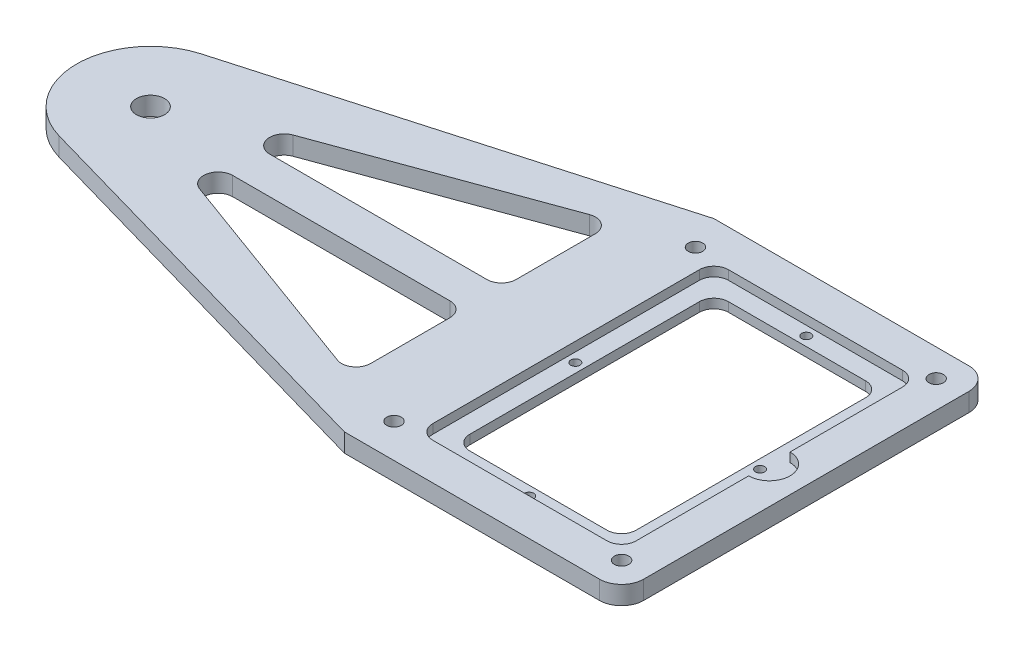
SolidWorks part; units mm, degrees
material "UHMW"
ref_plane "Front Plane" through (0, 0, 0) normal (0, 0, 1) x (1, 0, 0)
ref_plane "Top Plane" through (0, 0, 0) normal (0, 1, 0) x (1, 0, 0)
ref_plane "Right Plane" through (0, 0, 0) normal (1, 0, 0) x (0, 0, -1)
sketch "Sketch1" plane through (0, 0, 0) normal (0, 1, 0) x (1, 0, 0)
  line L0 (-47.625, 0) -> (47.625, 0) construction
  line L1 (-47.625, -63.5) -> (47.625, -63.5)
  line L2 (-47.625, -63.5) -> (-47.625, 63.5)
  line L3 (-47.625, 63.5) -> (47.625, 63.5)
  line L4 (47.625, -63.5) -> (47.625, 63.5)
  line L5 (-47.625, -63.5) -> (47.625, 63.5) construction
  line L6 (-47.625, 63.5) -> (47.625, -63.5) construction
  point P0 (0, 0)
  dimension "D1" = 95.25
  dimension "D2" = 127
  dimension "D3" = 63.5
extrude "Boss-Extrude1" add sketch "Sketch1" along normal blind 6.35
sketch "Sketch4" plane through (0, 6.35, 0) normal (0, 1, 0) x (1, 0, 0)
  line L1 (-47.625, 63.5) -> (-184.7599, 24.4278)
  line L5 (-47.625, 63.5) -> (-47.625, -63.5) construction
  line L9 (-47.625, -63.5) -> (-184.7599, -24.4278)
  line L10 (-47.625, 63.5) -> (-47.625, -63.5)
  arc A0 (-184.7599, 24.4278) -> (-184.7599, -24.4278) centre (-177.8, 0) ccw
  dimension "D1" = 50.8
  dimension "D2" = 177.8
extrude "Boss-Extrude3" add sketch "Sketch4" against normal blind 6.35
sketch "Sketch5" plane through (0, 6.35, 0) normal (0, 1, 0) x (1, 0, 0)
  circle A0 centre (-177.8, 0) radius 4.826
  circle A1 centre (-22.225, 0) radius 4.826
  arc A2 (-184.7599, 24.4278) -> (-184.7599, -24.4278) centre (-177.8, 0) ccw construction
  arc A3 (-184.7599, 24.4278) -> (-184.7599, -24.4278) centre (-177.8, 0) ccw
  dimension "D1" = 9.652
  dimension "D2" = 155.575
extrude "Cut-Extrude1" cut sketch "Sketch5" against normal through all contours A0 | A1
sketch "Sketch6" plane through (0, 6.35, 0) normal (0, 1, 0) x (1, 0, 0)
  line L0 (-63.5, 6.35) -> (-63.5, -6.35) construction
  line L1 (-63.5, 45.7715) -> (-171.45, 6.35)
  line L2 (-171.45, 6.35) -> (-63.5, 6.35)
  line L3 (-63.5, 6.35) -> (-63.5, 45.7715)
  line L4 (-63.5, -6.35) -> (-63.5, -45.7715)
  line L5 (-63.5, -45.7715) -> (-171.45, -6.35)
  line L6 (-171.45, -6.35) -> (-63.5, -6.35)
  line L7 (0, 0) -> (-63.5, 0) construction
  line L8 (-47.625, 63.5) -> (-184.7599, 24.4278) construction
  line L9 (-203.2, 78.2466) -> (-203.2, -78.2466) construction
  arc A1 (-184.7599, 24.4278) -> (-184.7599, -24.4278) centre (-177.8, 0) ccw construction
  point P2 (0, 0)
  point P10 (-203.2, 0)
  dimension "D1" = 12.7
  dimension "D2" = 31.75
  dimension "D3" = 12.7
  dimension "D4" = 63.5
extrude "Cut-Extrude2" cut sketch "Sketch6" against normal through all
fillet "Fillet9" radius 5 6 edges at (-171.45, 3.175, 6.35) (-63.5, 3.175, 6.35) (-63.5, 3.175, 45.7715) (-63.5, 3.175, -6.35) (-171.45, 3.175, -6.35) (-63.5, 3.175, -45.7715)
sketch "Sketch7" plane through (0, 6.35, 0) normal (0, 1, 0) x (1, 0, 0)
  circle A0 centre (-22.225, 0) radius 5.4538
extrude "Boss-Extrude4" add sketch "Sketch7" against normal blind 6.35
sketch "Sketch8" plane through (0, 6.35, 0) normal (0, 1, 0) x (1, 0, 0)
  line L4 (-47.625, -63.5) -> (47.625, -63.5) construction
  line L5 (-34.925, 50.8) -> (-34.925, -50.8)
  line L7 (-47.625, 63.5) -> (-47.625, -63.5) construction
  line L8 (-184.7599, -24.4278) -> (-47.625, -63.5) construction
  line L10 (47.625, 50.8) -> (-47.625, 50.8)
  line L11 (34.925, 50.8) -> (-34.925, 50.8)
  line L13 (34.925, -63.5) -> (34.925, 63.5)
  line L14 (34.925, -50.8) -> (34.925, 50.8)
  line L15 (-34.925, 63.5) -> (-34.925, -63.5) construction
  line L16 (-47.625, -50.8) -> (47.625, -50.8)
  line L17 (-34.925, -50.8) -> (34.925, -50.8)
  dimension "D1" = 12.7
  dimension "D2" = 12.7
  dimension "D3" = 12.7
  dimension "D4" = 12.7
extrude "Cut-Extrude3" cut sketch "Sketch8" against normal blind 3.175
sketch "Sketch9" plane through (0, 3.175, 0) normal (0, 1, 0) x (1, 0, 0)
  line L14 (-28.575, -44.45) -> (28.575, -44.45)
  line L15 (28.575, -44.45) -> (28.575, 44.45)
  line L16 (-28.575, 44.45) -> (-28.575, -44.45)
  line L17 (28.575, 44.45) -> (-28.575, 44.45)
  line L18 (-28.575, -44.45) -> (28.575, -44.45)
  line L19 (28.575, -44.45) -> (28.575, 44.45)
  line L20 (-28.575, 44.45) -> (-28.575, -44.45)
  line L21 (28.575, 44.45) -> (-28.575, 44.45)
  dimension "D1" = 6.35
extrude "Cut-Extrude4" cut sketch "Sketch9" against normal through all
sketch "Sketch11" plane through (0, 3.175, 0) normal (0, 1, 0) x (1, 0, 0)
  line L0 (0, 50.8) -> (0, -50.8) construction
  line L1 (34.925, 50.8) -> (-34.925, 50.8) construction
  line L2 (-34.925, -50.8) -> (34.925, -50.8) construction
  line L3 (-34.925, 0) -> (34.925, 0) construction
  line L4 (-34.925, 50.8) -> (-34.925, -50.8) construction
  line L5 (34.925, -50.8) -> (34.925, 50.8) construction
  line L6 (-34.925, 50.8) -> (-34.925, -50.8) construction
  line L7 (-28.575, 44.45) -> (-28.575, -44.45) construction
  line L8 (34.925, 50.8) -> (-34.925, 50.8) construction
  circle A0 centre (-31.75, 0) radius 1.5875
  circle A1 centre (31.75, 0) radius 1.5875
  circle A2 centre (0, 47.625) radius 1.5875
  circle A3 centre (0, -47.625) radius 1.5875
  dimension "D1" = 3.175
  dimension "D4" = 3.175
  dimension "D2" = 3.175
  dimension "D3" = 3.175
  dimension "D5" = 3.175
extrude "Cut-Extrude6" cut sketch "Sketch11" against normal through all
sketch "Sketch12" plane through (0, 6.35, 0) normal (0, 1, 0) x (1, 0, 0)
  line L0 (34.925, -50.8) -> (34.925, 50.8) construction
  line L1 (34.925, 7.112) -> (34.925, 50.8) construction
  line L2 (34.925, -7.112) -> (34.925, -50.8) construction
  line L3 (34.925, 0) -> (-34.925, 0) construction
  line L4 (-34.925, 50.8) -> (-34.925, -50.8) construction
  line L5 (34.925, -50.8) -> (34.925, 50.8) construction
  line L6 (34.925, 7.112) -> (34.925, -7.112)
  arc A0 (34.925, 7.112) -> (34.925, -7.112) centre (34.925, 0) cw
  dimension "D1" = 7.112
extrude "Cut-Extrude7" cut sketch "Sketch12" against normal blind 3.175
fillet "Fillet10" radius 5 4 edges at (-34.925, 4.7625, 50.8) (34.925, 4.7625, 50.8) (34.925, 4.7625, -50.8) (-34.925, 4.7625, -50.8)
fillet "Fillet11" radius 5 4 edges at (-28.575, 1.5875, -44.45) (28.575, 1.5875, -44.45) (28.575, 1.5875, 44.45) (-28.575, 1.5875, 44.45)
fillet "Fillet12" radius 7.62 2 edges at (47.625, 3.175, -63.5) (47.625, 3.175, 63.5)
sketch "Sketch13" plane through (0, 6.35, 0) normal (0, 1, 0) x (1, 0, 0)
  circle A0 centre (-42.2861, 51.8111) radius 2.4892
  circle A1 centre (-42.2861, -51.8111) radius 2.4892
  circle A2 centre (38.2023, -54.0773) radius 2.4892
  circle A3 centre (38.2023, 54.0773) radius 2.4892
  dimension "D1" = 4.9784
extrude "Cut-Extrude8" cut sketch "Sketch13" against normal through all
